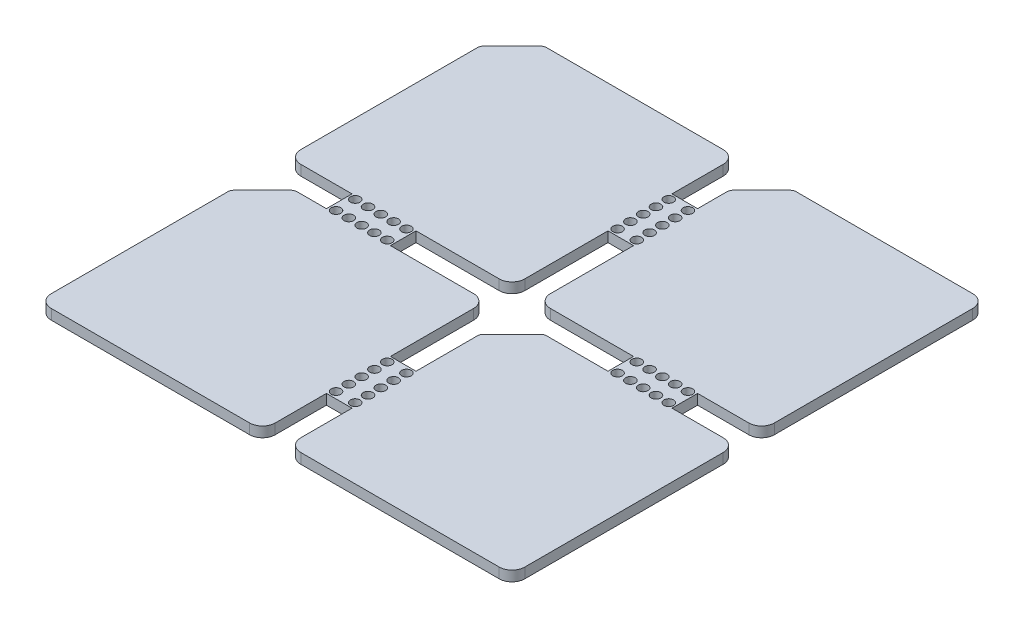
SolidWorks part; units mm, degrees
ref_plane "前视基准面" through (0, 0, 0) normal (0, 0, 1) x (1, 0, 0)
ref_plane "上视基准面" through (0, 0, 0) normal (0, 1, 0) x (1, 0, 0)
ref_plane "右视基准面" through (0, 0, 0) normal (1, 0, 0) x (0, 0, -1)
sketch "草图1" plane through (0, 0, 0) normal (0, 1, 0) x (1, 0, 0)
  line L0 (39, 0) -> (74, 0)
  line L1 (0, 0) -> (35, 0)
  line L2 (0, 0) -> (0, -35)
  line L3 (0, -35) -> (35, -35)
  line L4 (35, 0) -> (35, -35)
  line L9 (39, 0) -> (39, -35)
  line L10 (39, -35) -> (74, -35)
  line L11 (74, 0) -> (74, -35)
  line L12 (0, -39) -> (35, -39)
  line L13 (0, -39) -> (0, -74)
  line L14 (0, -74) -> (35, -74)
  line L15 (35, -39) -> (35, -74)
  line L16 (39, -39) -> (74, -39)
  line L17 (39, -39) -> (39, -74)
  line L18 (39, -74) -> (74, -74)
  line L19 (74, -39) -> (74, -74)
  dimension "D1" = 35
  dimension "D2" = 35
  dimension "D3" = 35
  dimension "D4" = 35
  dimension "D5" = 35
  dimension "D6" = 35
  dimension "D7" = 35
  dimension "D8" = 35
  dimension "D9" = 4
  dimension "D10" = 4
extrude "凸台-拉伸1" add sketch "草图1" along normal blind 1.6
sketch "草图2" plane through (0, 1.6, 0) normal (0, 1, 0) x (1, 0, 0)
  line L0 (0, -35) -> (35, -35) construction
  line L1 (10, -35) -> (20, -35)
  line L2 (10, -35) -> (10, -39)
  line L3 (10, -39) -> (20, -39)
  line L4 (20, -35) -> (20, -39)
  line L5 (35, -39) -> (0, -39) construction
  line L6 (35, -35) -> (35, 0) construction
  line L7 (35, -10) -> (39, -10)
  line L8 (35, -10) -> (35, -20)
  line L9 (35, -20) -> (39, -20)
  line L10 (39, -10) -> (39, -20)
  line L11 (39, 0) -> (39, -35) construction
  line L12 (39, -35) -> (74, -35) construction
  line L13 (54, -35) -> (64, -35)
  line L14 (54, -35) -> (54, -39)
  line L15 (54, -39) -> (64, -39)
  line L16 (64, -35) -> (64, -39)
  line L17 (74, -39) -> (39, -39) construction
  line L18 (35, -74) -> (35, -39) construction
  line L19 (35, -54) -> (39, -54)
  line L20 (35, -54) -> (35, -64)
  line L21 (35, -64) -> (39, -64)
  line L22 (39, -54) -> (39, -64)
  line L23 (39, -39) -> (39, -74) construction
  line L24 (0, 0) -> (0, -35) construction
  line L25 (35, 0) -> (0, 0) construction
  line L26 (74, -35) -> (74, 0) construction
  line L27 (39, -74) -> (74, -74) construction
  dimension "D1" = 10
  dimension "D2" = 10
  dimension "D3" = 10
  dimension "D4" = 10
  dimension "D5" = 10
  dimension "D6" = 10
  dimension "D7" = 10
  dimension "D8" = 10
extrude "凸台-拉伸2" add sketch "草图2" against normal up to surface (1.6 mm away) up to face at (17.5, 0, 17.5)
chamfer "倒角1" distance 5 angle 45 4 edges at (39, 0.8, 39) (0, 0.8, 39) (39, 0.8, 0) (0, 0.8, 0)
fillet "圆角1" radius 1 8 edges at (0, 0.8, 44) (5, 0.8, 39) (39, 0.8, 44) (44, 0.8, 39) (44, 0.8, 0) (39, 0.8, 5) (5, 0.8, 0) (0, 0.8, 5)
fillet "圆角2" radius 2 12 edges at (39, 0.8, 35) (35, 0.8, 39) (35, 0.8, 35) (74, 0.8, 0) (74, 0.8, 35) (74, 0.8, 39) (74, 0.8, 74) (39, 0.8, 74) (35, 0.8, 74) (0, 0.8, 74) (0, 0.8, 35) (35, 0.8, 0)
sketch "草图3" plane through (0, 1.6, 0) normal (0, 1, 0) x (1, 0, 0)
  line L0 (2, -35) -> (10, -35) construction
  line L1 (10, -35) -> (10, -39) construction
  line L2 (4.7277, -37) -> (75.5352, -37) construction
  line L3 (64, -39) -> (64, -35) construction
  line L4 (64, -35) -> (72, -35) construction
  circle A0 centre (11, -35.5) radius 0.75
  circle A1 centre (63, -35.5) radius 0.75
  circle A2 centre (63, -38.5) radius 0.75
  circle A3 centre (11, -38.5) radius 0.75
  circle A4 centre (13, -38.5) radius 0.75
  circle A5 centre (13, -35.5) radius 0.75
  circle A6 centre (15, -38.5) radius 0.75
  circle A7 centre (15, -35.5) radius 0.75
  circle A8 centre (17, -38.5) radius 0.75
  circle A9 centre (17, -35.5) radius 0.75
  circle A10 centre (19, -38.5) radius 0.75
  circle A11 centre (19, -35.5) radius 0.75
  circle A12 centre (61, -35.5) radius 0.75
  circle A13 centre (61, -38.5) radius 0.75
  circle A14 centre (59, -35.5) radius 0.75
  circle A15 centre (59, -38.5) radius 0.75
  circle A16 centre (57, -35.5) radius 0.75
  circle A17 centre (57, -38.5) radius 0.75
  circle A18 centre (55, -35.5) radius 0.75
  circle A19 centre (55, -38.5) radius 0.75
  point P11 (64, -37)
  dimension "D1" = 1.5
  dimension "D4" = 1.5
  dimension "D2" = 0.5
  dimension "D3" = 1
  dimension "D5" = 0.5
  dimension "D6" = 1
  dimension "D8" = 2
  dimension "D10" = 2
  dimension "D7" = 5
  dimension "D9" = 5
extrude "切除-拉伸1" cut sketch "草图3" against normal through all
sketch "草图4" plane through (0, 1.6, 0) normal (0, 1, 0) x (1, 0, 0)
  line L0 (35, -10) -> (35, -2) construction
  line L1 (39, -10) -> (35, -10) construction
  line L2 (39, -5.4142) -> (39, -10) construction
  line L3 (35, -72) -> (35, -64) construction
  line L4 (39, -64) -> (39, -72) construction
  line L5 (35, -64) -> (39, -64) construction
  circle A0 centre (35.5, -11) radius 0.75
  circle A1 centre (38.5, -11) radius 0.75
  circle A2 centre (35.5, -13) radius 0.75
  circle A3 centre (38.5, -13) radius 0.75
  circle A4 centre (35.5, -15) radius 0.75
  circle A5 centre (38.5, -15) radius 0.75
  circle A6 centre (35.5, -17) radius 0.75
  circle A7 centre (38.5, -17) radius 0.75
  circle A8 centre (35.5, -19) radius 0.75
  circle A9 centre (38.5, -19) radius 0.75
  circle A10 centre (35.5, -63) radius 0.75
  circle A11 centre (38.5, -63) radius 0.75
  circle A12 centre (35.5, -61) radius 0.75
  circle A13 centre (38.5, -61) radius 0.75
  circle A14 centre (35.5, -59) radius 0.75
  circle A15 centre (38.5, -59) radius 0.75
  circle A16 centre (35.5, -57) radius 0.75
  circle A17 centre (38.5, -57) radius 0.75
  circle A18 centre (35.5, -55) radius 0.75
  circle A19 centre (38.5, -55) radius 0.75
  dimension "D1" = 1.5
  dimension "D8" = 1.5
  dimension "D2" = 0.5
  dimension "D3" = 1
  dimension "D4" = 0.5
  dimension "D5" = 1
  dimension "D7" = 2
  dimension "D9" = 0.5
  dimension "D10" = 0.5
  dimension "D11" = 1
  dimension "D12" = 1
  dimension "D14" = 2
  dimension "D6" = 5
  dimension "D13" = 5
extrude "切除-拉伸2" cut sketch "草图4" against normal through all
